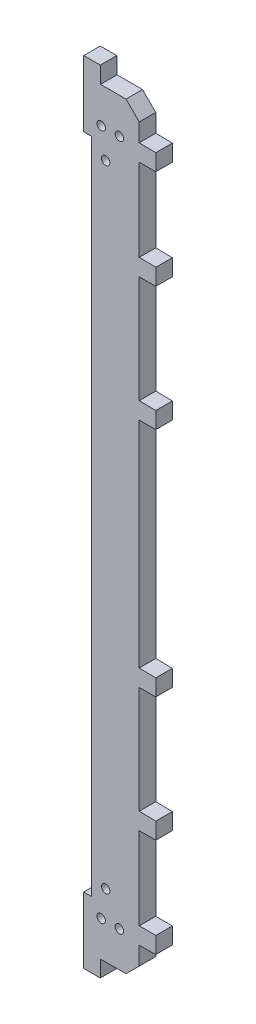
SolidWorks part; units mm, degrees
ref_plane "Front" through (0, 0, 0) normal (0, 0, 1) x (1, 0, 0)
ref_plane "Top" through (0, 0, 0) normal (0, 1, 0) x (1, 0, 0)
ref_plane "Right" through (0, 0, 0) normal (1, 0, 0) x (0, 0, -1)
sketch "Эскиз1" plane through (0, 0, 0) normal (0, 0, 1) x (1, 0, 0)
  line L0 (-16.9786, 199) -> (-16.9786, -199)
  line L1 (-21.7659, 238.9986) -> (-21.7993, 229)
  line L2 (-11.7659, 238.9986) -> (-21.7659, 238.9986)
  line L3 (-11.5993, 229) -> (-11.7659, 238.9986)
  line L4 (3.8007, 229) -> (-11.5993, 229)
  line L5 (11.8007, 221) -> (3.8007, 229)
  line L6 (11.8007, 210.1) -> (11.8007, 221)
  line L7 (21.7993, 209.9334) -> (11.8007, 210.1)
  line L8 (21.7993, 199.9334) -> (21.7993, 209.9334)
  line L9 (11.8007, 199.9) -> (21.7993, 199.9334)
  line L10 (11.8007, 176.55) -> (11.8007, 199.9)
  line L11 (11.8007, 150.1) -> (11.8007, 176.55)
  line L12 (21.7993, 149.9334) -> (11.8007, 150.1)
  line L13 (21.7993, 139.9334) -> (21.7993, 149.9334)
  line L14 (11.8007, 139.9) -> (21.7993, 139.9334)
  line L15 (11.8007, 109.05) -> (11.8007, 139.9)
  line L16 (11.8007, 75.1) -> (11.8007, 109.05)
  line L17 (21.7993, 74.9334) -> (11.8007, 75.1)
  line L18 (21.7993, 64.9334) -> (21.7993, 74.9334)
  line L19 (11.8007, 64.9) -> (21.7993, 64.9334)
  line L20 (11.8007, -64.9) -> (11.8007, 64.9)
  line L21 (21.7993, -65.0666) -> (11.8007, -64.9)
  line L22 (21.7993, -75.0666) -> (21.7993, -65.0666)
  line L23 (11.8007, -75.1) -> (21.7993, -75.0666)
  line L24 (11.8007, -105.95) -> (11.8007, -75.1)
  line L25 (11.8007, -139.9) -> (11.8007, -105.95)
  line L26 (21.7993, -140.0666) -> (11.8007, -139.9)
  line L27 (21.7993, -150.0666) -> (21.7993, -140.0666)
  line L28 (11.8007, -150.1) -> (21.7993, -150.0666)
  line L29 (11.8007, -173.45) -> (11.8007, -150.1)
  line L30 (11.8007, -199.9) -> (11.8007, -173.45)
  line L31 (21.7993, -199.9334) -> (11.8007, -199.9)
  line L32 (21.7993, -209.9334) -> (21.7993, -199.9334)
  line L33 (11.8007, -210.1) -> (21.7993, -209.9334)
  line L34 (11.8007, -221) -> (11.8007, -210.1)
  line L35 (3.8007, -229) -> (11.8007, -221)
  line L36 (-11.5993, -229) -> (3.8007, -229)
  line L37 (-11.7659, -238.9986) -> (-11.5993, -229)
  line L38 (-21.7659, -238.9986) -> (-11.7659, -238.9986)
  line L39 (-21.7993, -229) -> (-21.7659, -238.9986)
  line L40 (-21.7993, -229) -> (-21.7993, -199)
  line L41 (-21.7993, -199) -> (-16.9786, -199)
  line L42 (-21.7993, 229) -> (-21.7993, 199)
  line L43 (-21.7993, 199) -> (-16.9786, 199)
  circle A0 centre (-11.1993, -207.5) radius 2.55
  circle A1 centre (-11.1993, 207.5) radius 2.55
  circle A2 centre (-0.1993, 207.5) radius 2.55
  circle A3 centre (-8.4888, 190.6472) radius 2.55
  circle A4 centre (-0.1993, -207.5) radius 2.55
  circle A5 centre (-8.4888, -190.65) radius 2.55
extrude "Бобышка-Вытянуть1" add sketch "Эскиз1" along normal blind 10
